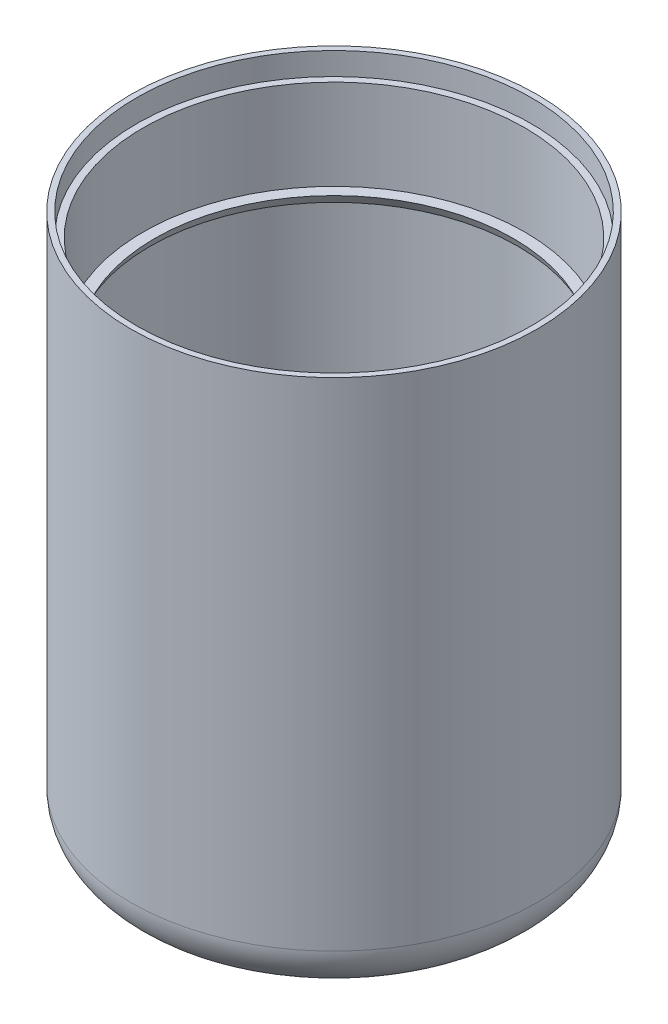
SolidWorks part; units mm, degrees
ref_plane "Front Plane" through (0, 0, 0) normal (0, 0, 1) x (1, 0, 0)
ref_plane "Top Plane" through (0, 0, 0) normal (0, 1, 0) x (1, 0, 0)
ref_plane "Right Plane" through (0, 0, 0) normal (1, 0, 0) x (0, 0, -1)
sketch "Sketch1" plane through (0, 0, 0) normal (1, 0, 0) x (0, 0, -1)
  line L0 (0, 48.808) -> (0, -60) construction
  line L3 (-45, 55) -> (-45, -55)
  line L4 (-35, -65) -> (-15, -65)
  line L6 (-40.75, -15) -> (-40.75, 28)
  line L7 (-42.25, 30) -> (-39.75, 30)
  line L9 (-45, 55) -> (-43.75, 55)
  line L12 (-43.75, 50) -> (-40.75, 50)
  line L17 (-40, 10) -> (0, 10) construction
  line L25 (-43.75, 50) -> (-43.75, 55)
  line L28 (-40, -18.0311) -> (-40, -50)
  line L29 (-42.25, 30) -> (-42.25, 50)
  line L30 (-40, -18.0311) -> (-38.25, -15)
  line L31 (-40.75, -15) -> (-38.25, -15)
  line L32 (-40.75, 28) -> (-39.75, 30)
  line L33 (-4, -70) -> (-4, -80)
  line L34 (-40.75, 28) -> (-40.75, 30) construction
  line L35 (-5, -75) -> (-5, -80)
  line L36 (-5, -80) -> (-4, -80)
  line L37 (-30, -60) -> (-14, -60)
  arc A0 (-5, -75) -> (-15, -65) centre (-15, -75) ccw
  arc A1 (-14, -60) -> (-4, -70) centre (-14, -70) cw
  arc A2 (-40, -50) -> (-30, -60) centre (-30, -50) ccw
  arc A3 (-45, -55) -> (-35, -65) centre (-35, -55) ccw
  point P9 (-45, 0)
  point P37 (-45, -65)
  dimension "D16" = 10
  dimension "D13" = 10
  dimension "D17" = 10
  dimension "D1" = 1.5
  dimension "D2" = 45
  dimension "D3" = 120
  dimension "D4" = 2.5
  dimension "D5" = 5
  dimension "D6" = 5
  dimension "D7" = 87.5
  dimension "D8" = 5
  dimension "D9" = 2.5
  dimension "D10" = 30
  dimension "D11" = 2
  dimension "D12" = 45
  dimension "D14" = 4
  dimension "D15" = 1
  dimension "D18" = 15
revolve "Revolve1" add sketch "Sketch1" angle 360 about L0
sketch "Sketch2" plane through (0, 0, 0) normal (0, 0, 1) x (1, 0, 0)
  line L0 (43.75, 55) -> (-43.75, 55) construction
  circle A0 centre (0, -10) radius 3
  dimension "D1" = 65
  dimension "D2" = 6
extrude "Cut-Extrude1" cut sketch "Sketch2" against normal through all
